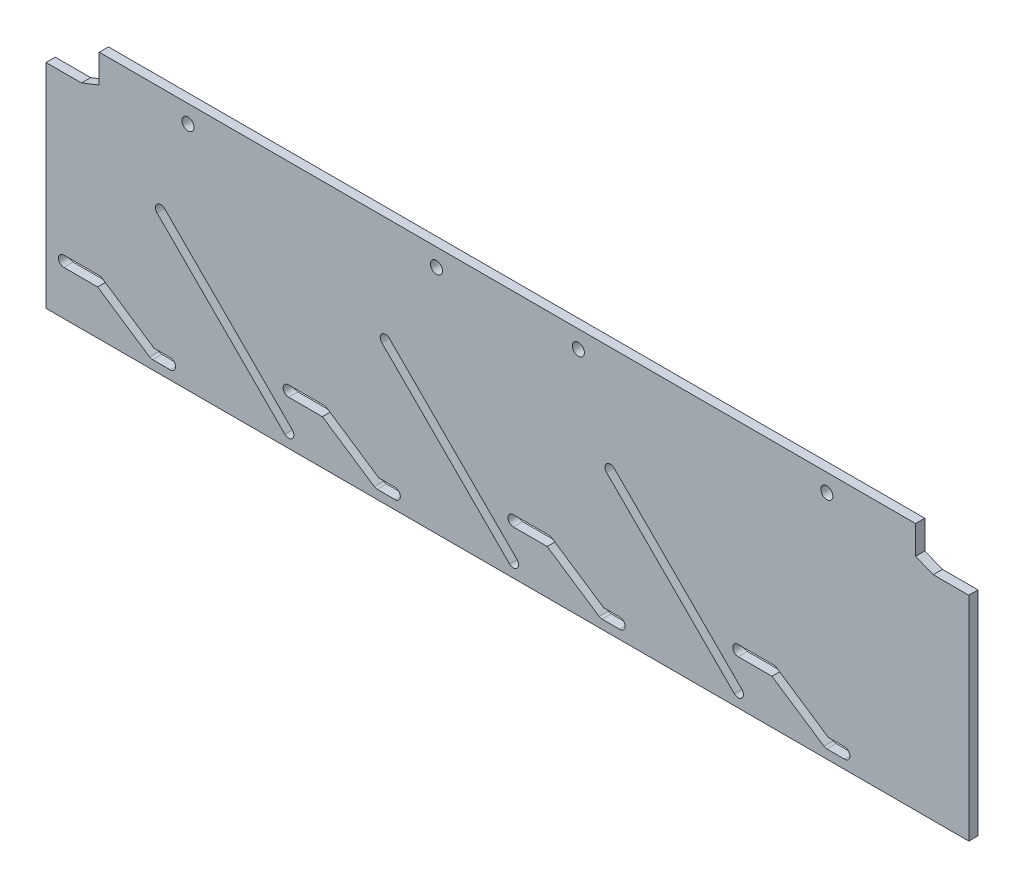
SolidWorks part; units mm, degrees
ref_plane "前视基准面" through (0, 0, 0) normal (0, 0, 1) x (1, 0, 0)
ref_plane "上视基准面" through (0, 0, 0) normal (0, 1, 0) x (1, 0, 0)
ref_plane "右视基准面" through (0, 0, 0) normal (1, 0, 0) x (0, 0, -1)
sketch "草图1" plane through (0, 0, 0) normal (0, 0, 1) x (1, 0, 0)
  line L1 (-130, 35) -> (130, 35)
  line L2 (-130, 35) -> (-130, -35)
  line L3 (-130, -35) -> (130, -35)
  line L4 (130, 35) -> (130, -35)
  line L5 (-130, 35) -> (130, -35) construction
  line L6 (-130, -35) -> (130, 35) construction
  point P0 (0, 0)
  dimension "D1" = 70
  dimension "D2" = 260
extrude "凸台-拉伸1" add sketch "草图1" along normal blind 2.6
sketch "草图2" plane through (0, 0, 2.6) normal (0, 0, 1) x (1, 0, 0)
  line L0 (-90, 30) -> (-20, 30) construction
  line L1 (-20, 30) -> (20, 30) construction
  line L2 (20, 30) -> (90, 30) construction
  line L4 (-130, -35) -> (130, -35) construction
  line L5 (-130, 35) -> (-130, -35) construction
  line L6 (130, -35) -> (130, 35) construction
  line L8 (130, 35) -> (-130, 35) construction
  line L9 (-130, 25) -> (-130, 35)
  line L10 (-130, 35) -> (-115, 35)
  line L12 (130, 25) -> (130, 35)
  line L13 (130, 35) -> (115, 35)
  line L14 (-130, 25) -> (-120, 25)
  line L15 (-120, 25) -> (-115, 27)
  line L16 (-115, 27) -> (-115, 35)
  line L17 (115, 35) -> (115, 27)
  line L18 (115, 27) -> (120, 25)
  line L19 (120, 25) -> (130, 25)
  circle A0 centre (-90, 30) radius 1.7
  circle A1 centre (-20, 30) radius 1.7
  circle A2 centre (20, 30) radius 1.7
  circle A3 centre (90, 30) radius 1.7
  point P28 (0, 0)
  dimension "D1" = 3.4
  dimension "D2" = 65
  dimension "D3" = 40
  dimension "D4" = 40
  dimension "D5" = 70
  dimension "D6" = 70
  dimension "D7" = 15
  dimension "D8" = 10
  dimension "D9" = 8
  dimension "D10" = 10
extrude "切除-拉伸1" cut sketch "草图2" against normal through all
sketch "草图3" plane through (0, 0, 2.6) normal (0, 0, 1) x (1, 0, 0)
  line L0 (-95, -31) -> (-61.6667, -31) construction
  line L1 (-61.6667, -31) -> (-31.6667, -31) construction
  line L2 (-31.6667, -31) -> (1.6667, -31) construction
  line L3 (1.6667, -31) -> (31.6667, -31) construction
  line L4 (31.6667, -31) -> (65, -31) construction
  line L5 (65, -31) -> (95, -31) construction
  line L6 (95, -31) -> (128.3333, -31) construction
  line L7 (130, -35) -> (130, 25) construction
  line L10 (-130, -35) -> (130, -35) construction
  line L11 (-125, -31) -> (-95, -31) construction
  line L14 (-130, 25) -> (-130, -35) construction
  circle A0 centre (-61.6667, -31) radius 1.3
  circle A1 centre (1.6667, -31) radius 1.3
  circle A2 centre (65, -31) radius 1.3
  circle A3 centre (-95, -31) radius 1.3 construction
  circle A4 centre (-31.6667, -31) radius 1.3 construction
  circle A5 centre (31.6667, -31) radius 1.3 construction
  circle A6 centre (95, -31) radius 1.3 construction
  circle A11 centre (-125, -31) radius 1.9563 construction
  point P17 (0, 0)
  point P20 (0, 0)
  point P21 (108.3333, -31)
  dimension "D1" = 2.6
  dimension "D7" = 63.3333
  dimension "D3" = 35
  dimension "D2" = 5
  dimension "D4" = 4
  dimension "D5" = 65
extrude "切除-拉伸2" cut sketch "草图3" against normal through all
sketch "草图5" plane through (0, 0, 2.6) normal (0, 0, 1) x (1, 0, 0)
  line L0 (-61.6667, -31) -> (-97.6667, 5) construction
  line L1 (-62.7273, -32.0607) -> (-98.7273, 3.9393)
  line L2 (-60.606, -29.9393) -> (-96.606, 6.0607)
  line L3 (-95, -31) -> (-61.6667, -31) construction
  line L4 (-130, -35) -> (130, -35) construction
  arc A0 (-62.7273, -32.0607) -> (-60.606, -29.9393) centre (-61.6667, -31) ccw
  arc A1 (-96.606, 6.0607) -> (-98.7273, 3.9393) centre (-97.6667, 5) ccw
  point P3 (-79.6667, -13)
  dimension "D1" = 3
  dimension "D2" = 45
  dimension "40" = 40
extrude "切除-拉伸4" cut sketch "草图5" against normal through all
pattern_linear "阵列(线性)2" count 3 spacing 63.3333 along (1, 0, 0) of "切除-拉伸4"
sketch "草图4" plane through (0, 0, 2.6) normal (0, 0, 1) x (1, 0, 0)
  line L0 (-125, -21) -> (-115, -21) construction
  line L1 (-125, -19.5) -> (-115, -19.5)
  line L2 (-125, -22.5) -> (-115.4542, -22.5)
  line L3 (-115, -21) -> (-100, -31) construction
  line L4 (-114.1679, -19.7519) -> (-99.5458, -29.5)
  line L5 (-115.4542, -22.5) -> (-100.8321, -32.2481)
  line L7 (-125, -31) -> (-95, -31) construction
  line L8 (-100, -31) -> (-95, -31) construction
  line L9 (-99.5458, -29.5) -> (-95, -29.5)
  line L10 (-100, -32.5) -> (-95, -32.5)
  arc A0 (-125, -19.5) -> (-125, -22.5) centre (-125, -21) ccw
  arc A2 (-114.1679, -19.7519) -> (-115, -19.5) centre (-115, -21) ccw
  arc A4 (-100.8321, -32.2481) -> (-100, -32.5) centre (-100, -31) ccw
  arc A5 (-95, -32.5) -> (-95, -29.5) centre (-95, -31) ccw
  point P2 (-132.5, -21)
  point P7 (-117.5, -26)
  point P20 (-105, -31)
  dimension "D1" = 10
  dimension "D2" = 10
  dimension "D3" = 3
  dimension "D4" = 3
  dimension "D5" = 3
  dimension "D6" = 5
extrude "切除-拉伸3" cut sketch "草图4" against normal through all
pattern_linear "阵列(线性)1" count 4 spacing 63.3333 along (1, 0, 0) of "切除-拉伸3"
